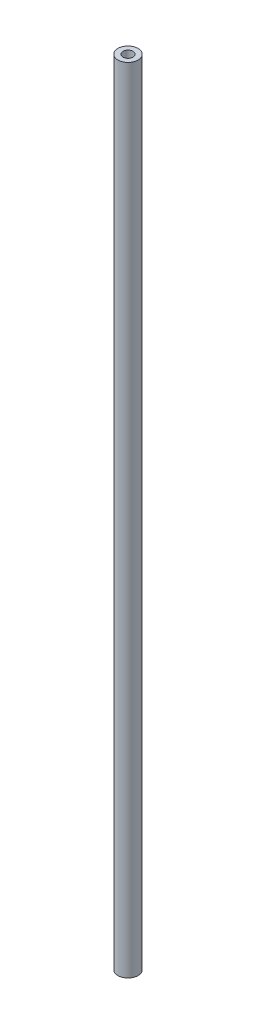
SolidWorks part; units mm, degrees
material "Fr-4"
ref_plane "Front Plane" through (0, 0, 0) normal (0, 0, 1) x (1, 0, 0)
ref_plane "Top Plane" through (0, 0, 0) normal (0, 1, 0) x (1, 0, 0)
ref_plane "Right Plane" through (0, 0, 0) normal (1, 0, 0) x (0, 0, -1)
sketch "Sketch1" plane through (0, 0, 0) normal (0, 1, 0) x (1, 0, 0)
  circle A0 centre (0, 0) radius 3.175
  circle A1 centre (0, 0) radius 1.5875
  dimension "D1" = 6.35
  dimension "D2" = 3.175
extrude "Boss-Extrude1" add sketch "Sketch1" along normal blind 250
